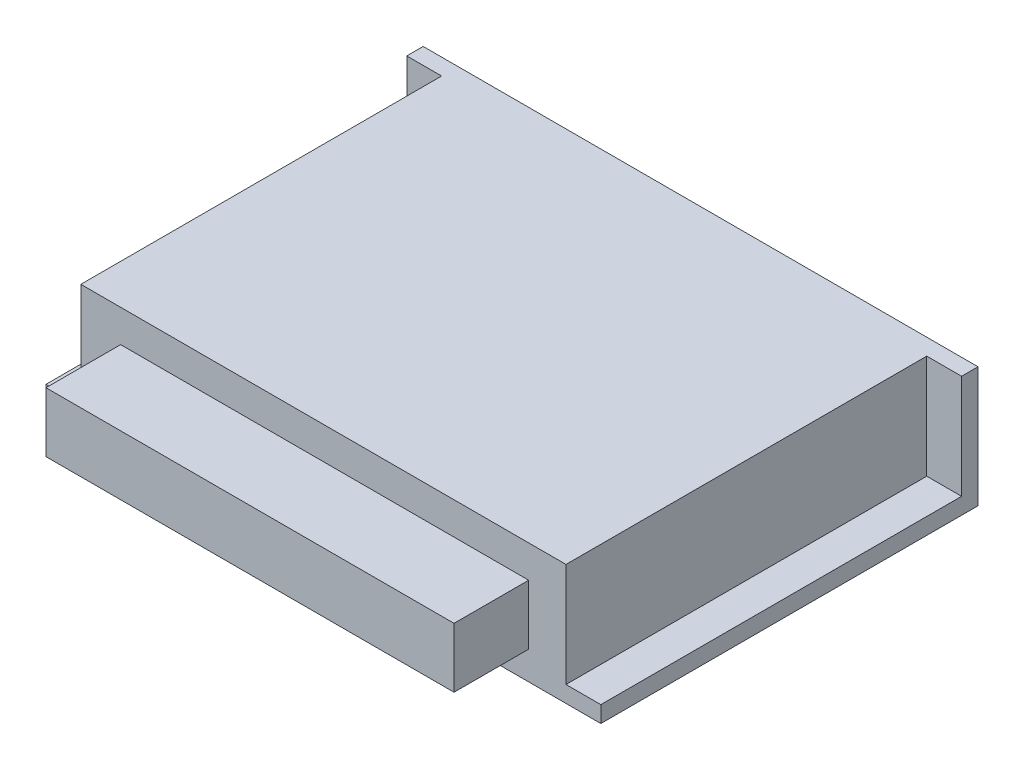
SolidWorks part; units mm, degrees
ref_plane "Front" through (0, 0, 0) normal (0, 0, 1) x (1, 0, 0)
ref_plane "Top" through (0, 0, 0) normal (0, 1, 0) x (1, 0, 0)
ref_plane "Right" through (0, 0, 0) normal (1, 0, 0) x (0, 0, -1)
sketch "Sketch1" plane through (0, 0, 0) normal (0, 1, 0) x (1, 0, 0)
  line L1 (-55.75, -37.9) -> (55.75, -37.9)
  line L2 (-55.75, -37.9) -> (-55.75, 37.9)
  line L3 (-55.75, 37.9) -> (55.75, 37.9)
  line L4 (55.75, -37.9) -> (55.75, 37.9)
  line L5 (-55.75, -37.9) -> (55.75, 37.9) construction
  line L6 (-55.75, 37.9) -> (55.75, -37.9) construction
  point P0 (0, 0)
  dimension "D1" = 111.5
  dimension "D2" = 75.8
extrude "Boss-Extrude1" add sketch "Sketch1" along normal blind 3.3
sketch "Sketch2" plane through (0, 3.3, 0) normal (0, 1, 0) x (1, 0, 0)
  line L0 (55.75, 37.9) -> (-55.75, 37.9) construction
  line L1 (-48.75, 37.9) -> (48.75, 37.9)
  line L2 (-48.75, 34.6) -> (-48.75, -37.9)
  line L3 (-48.75, -37.9) -> (48.75, -37.9)
  line L4 (48.75, 34.6) -> (48.75, -37.9)
  line L5 (-55.75, 37.9) -> (-55.75, -37.9) construction
  line L6 (-55.75, -37.9) -> (55.75, -37.9) construction
  line L7 (55.75, -37.9) -> (55.75, 37.9) construction
  line L8 (-55.75, 37.9) -> (55.75, 37.9)
  line L9 (-55.75, 37.9) -> (-55.75, 34.6)
  line L10 (-55.75, 34.6) -> (-48.75, 34.6)
  line L11 (55.75, 37.9) -> (55.75, 34.6)
  line L12 (48.75, 34.6) -> (55.75, 34.6)
  point P6 (0, -37.9)
  line M10 (55.75, -37.9) -> (55.75, 37.9)
  line M11 (55.75, 37.9) -> (-55.75, 37.9)
  line M12 (-55.75, 37.9) -> (-55.75, -37.9)
  line M13 (-55.75, -37.9) -> (55.75, -37.9)
  dimension "D1" = 7
  dimension "D2" = 3.3
extrude "Boss-Extrude2" add sketch "Sketch2" along normal offset from surface (20.9 mm away) 24.2 contours L4 L12 L10 L2 M10 M11 M12 M13 up to face at (0, 0, 0)
sketch "Sketch3" plane through (0, 0, 37.9) normal (0, 0, 1) x (1, 0, 0)
  line L1 (-40.75, 5.7) -> (41.25, 5.7)
  line L2 (-40.75, 5.7) -> (-40.75, 17.7)
  line L3 (-40.75, 17.7) -> (41.25, 17.7)
  line L4 (41.25, 5.7) -> (41.25, 17.7)
  line L5 (-48.75, 24.2) -> (-48.75, 3.3) construction
  line L6 (48.75, 24.2) -> (-48.75, 24.2) construction
  dimension "D1" = 82
  dimension "D2" = 8
  dimension "D3" = 6.5
  dimension "D4" = 12
extrude "Boss-Extrude3" add sketch "Sketch3" along normal blind 15
